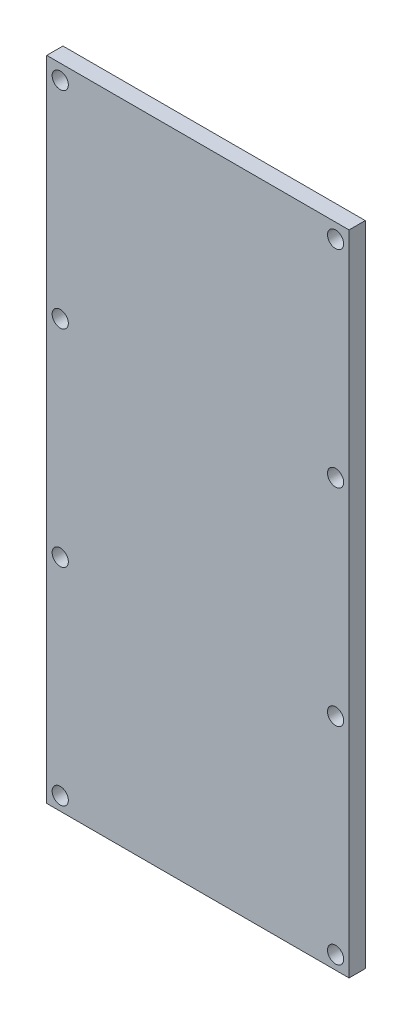
SolidWorks part; units mm, degrees
ref_plane "Přední rovina" through (0, 0, 0) normal (0, 0, 1) x (1, 0, 0)
ref_plane "Horní rovina" through (0, 0, 0) normal (0, 1, 0) x (1, 0, 0)
ref_plane "Pravá rovina" through (0, 0, 0) normal (1, 0, 0) x (0, 0, -1)
sketch "Skica1" plane through (0, 0, 0) normal (0, 0, 1) x (1, 0, 0)
  line L0 (-60.5, -10.5) -> (-60.5, 27.75) construction
  line L1 (-58, 107) -> (-114, 107)
  line L2 (-58, 107) -> (-58, -13)
  line L3 (-58, -13) -> (-114, -13)
  line L4 (-114, 107) -> (-114, -13)
  circle A0 centre (-60.5, -10.5) radius 1.5
  circle A1 centre (-111.5, -10.5) radius 1.5
  circle A2 centre (-111.5, 27.75) radius 1.5
  circle A3 centre (-111.5, 66) radius 1.5
  circle A4 centre (-111.5, 104.25) radius 1.5
  circle A5 centre (-60.5, 27.75) radius 1.5
  circle A6 centre (-60.5, 66) radius 1.5
  circle A7 centre (-60.5, 104.25) radius 1.5
  dimension "D1" = 3
  dimension "D4" = 38.25
  dimension "D2" = 2
  dimension "D3" = 4
extrude "Přidat vysunutím1" add sketch "Skica1" along normal blind 3
sketch "Skica2" plane through (0, 0, 3) normal (0, 0, 1) x (1, 0, 0)
  line L0 (-63, 102) -> (-63, -8)
  line L1 (-58, 107) -> (-114, 107)
  line L2 (-58, 107) -> (-58, -13)
  line L3 (-58, -13) -> (-114, -13)
  line L4 (-114, 107) -> (-114, -13)
  line L5 (-63, -8) -> (-109, -8)
  line L6 (-109, 102) -> (-109, -8)
  line L7 (-63, 102) -> (-109, 102)
  line L8 (-64.5, 100.5) -> (-107.5, 100.5)
  line L9 (-107.5, 100.5) -> (-107.5, -6.5)
  line L10 (-64.5, -6.5) -> (-107.5, -6.5)
  line L11 (-64.5, 100.5) -> (-64.5, -6.5)
  dimension "D1" = 5
  dimension "D2" = 1.5
extrude "Přidat vysunutím2" add sketch "Skica2" against normal blind 6 contours L0 L7 L6 L5 L8 L11 L10 L9
